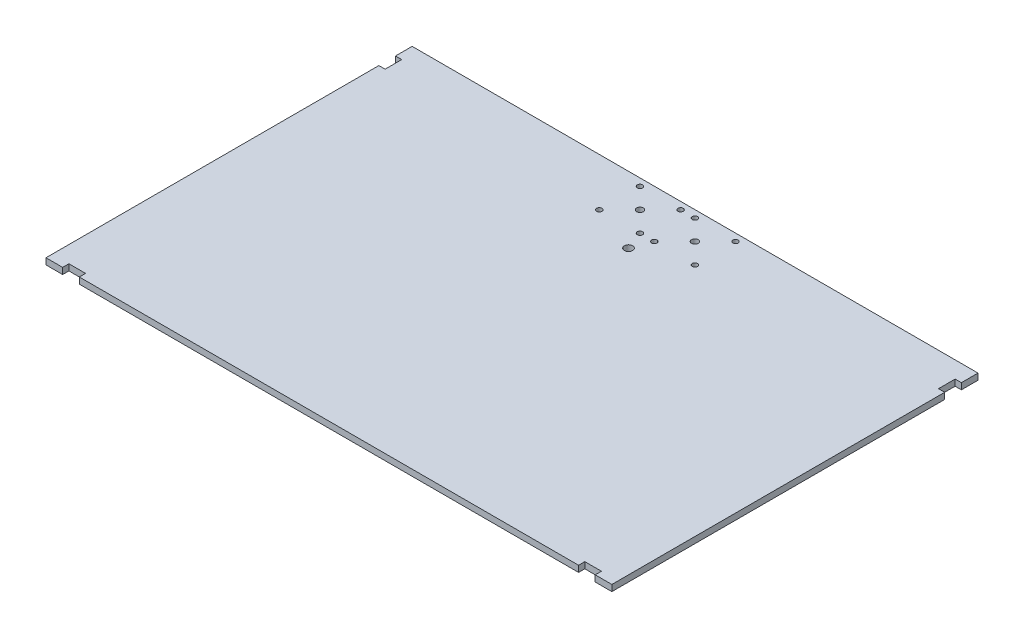
SolidWorks part; units mm, degrees
ref_plane "Front" through (0, 0, 0) normal (0, 0, 1) x (1, 0, 0)
ref_plane "Top" through (0, 0, 0) normal (0, 1, 0) x (1, 0, 0)
ref_plane "Right" through (0, 0, 0) normal (1, 0, 0) x (0, 0, -1)
sketch "Sketch1" plane through (0, 0, 0) normal (0, 1, 0) x (1, 0, 0)
  line L0 (215.9, 279.4) -> (215.9, 228.6) construction
  line L1 (0, 0) -> (12.7, 0)
  line L2 (0, 0) -> (0, 254)
  line L3 (0, 279.4) -> (431.8, 279.4)
  line L4 (431.8, 0) -> (431.8, 254)
  line L5 (194.945, 260.858) -> (194.945, 255.778) construction
  line L6 (192.405, 258.318) -> (197.485, 258.318) construction
  line L7 (0, 254) -> (4.7625, 254)
  line L8 (431.8, 266.7) -> (427.0375, 266.7)
  line L10 (431.8, 254) -> (427.0375, 254)
  line L11 (427.0375, 266.7) -> (427.0375, 254)
  line L12 (4.7625, 266.7) -> (4.7625, 254)
  line L13 (0, 266.7) -> (4.7625, 266.7)
  line L15 (431.8, 266.7) -> (431.8, 279.4)
  line L16 (0, 266.7) -> (0, 279.4)
  line L17 (25.4, 0) -> (406.4, 0)
  line L19 (12.7, 0) -> (12.7, 4.7625)
  line L20 (12.7, 4.7625) -> (25.4, 4.7625)
  line L21 (25.4, 0) -> (25.4, 4.7625)
  line L22 (406.4, 0) -> (406.4, 4.7625)
  line L23 (419.1, 4.7625) -> (406.4, 4.7625)
  line L24 (419.1, 0) -> (419.1, 4.7625)
  line L25 (419.1, 0) -> (431.8, 0)
  circle A0 centre (215.9, 228.6) radius 3.175
  circle A1 centre (210.439, 273.812) radius 2.032
  circle A2 centre (179.451, 273.812) radius 2.032
  circle A3 centre (252.349, 273.812) radius 2.032
  circle A4 centre (221.361, 273.812) radius 2.032
  circle A5 centre (194.945, 258.318) radius 2.54
  circle A7 centre (210.439, 242.824) radius 2.032
  circle A8 centre (179.451, 242.824) radius 2.032
  circle A9 centre (221.361, 242.824) radius 2.032
  circle A10 centre (236.855, 258.318) radius 2.54
  circle A11 centre (252.349, 242.824) radius 2.032
  point P44 (12.7, 2.3813)
  dimension "D4" = 6.35
  dimension "D5" = 4.064
  dimension "D10" = 5.08
  dimension "D1" = 279.4
  dimension "D2" = 431.8
  dimension "D3" = 50.8
  dimension "D6" = 5.588
  dimension "D7" = 30.988
  dimension "D8" = 30.988
  dimension "D9" = 72.898
  dimension "D11" = 30.988
  dimension "D12" = 4.7625
  dimension "D13" = 12.7
  dimension "D14" = 12.7
  dimension "D15" = 4.7625
  dimension "D16" = 12.7
  dimension "D17" = 12.7
extrude "Boss-Extrude1" add sketch "Sketch1" along normal blind 4.7625
